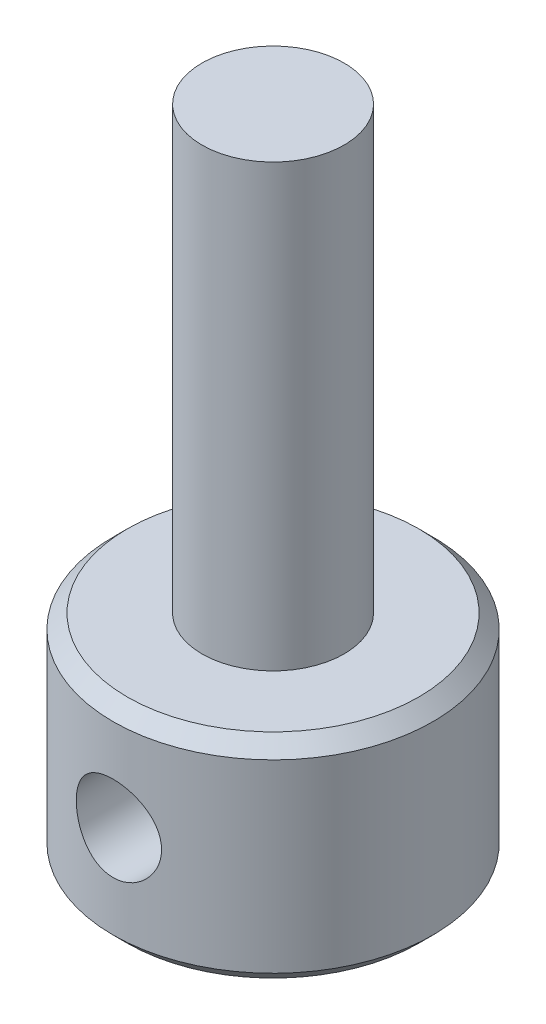
SolidWorks part; units mm, degrees
ref_plane "前视基准面" through (0, 0, 0) normal (0, 0, 1) x (1, 0, 0)
ref_plane "上视基准面" through (0, 0, 0) normal (0, 1, 0) x (1, 0, 0)
ref_plane "右视基准面" through (0, 0, 0) normal (1, 0, 0) x (0, 0, -1)
sketch "草图1" plane through (0, 0, 0) normal (0, 1, 0) x (1, 0, 0)
  circle A0 centre (0, 0) radius 11.25
  dimension "D1" = 22.5
extrude "凸台-拉伸1" add sketch "草图1" along normal blind 15
sketch "草图2" plane through (0, 15, 0) normal (0, 1, 0) x (1, 0, 0)
  circle A0 centre (0, 0) radius 5
  dimension "D1" = 10
extrude "凸台-拉伸2" add sketch "草图2" along normal blind 31
chamfer "倒角1" distance 1 angle 45 2 edges at (0, 0, 11.25) (0, 15, 11.25)
hole_wizard "Ø6.0mm 暗销孔2" positions "3D草图1" profile "草图3" hole size "Ø6.0" standard "GB" end condition through all
sketch3d "3D草图1"
  point P0 (0, 7.5, 11.25)
  dimension "D1" = 38.5
sketch "草图3" plane through (0, 7.5, 11.25) normal (1, 0, 0) x (0, -1, 0)
  line L0 (0, 0) -> (0, 22.5)
  line L1 (0, 22.5) -> (3, 22.5)
  line L2 (3, 22.5) -> (3, 0)
  line L5 (3, 0) -> (0, 0)
  line L11 (0, -6.35) -> (0, 107.95) construction
  dimension "通孔孔直径" = 6
  dimension "通孔孔深度" = 22.5
